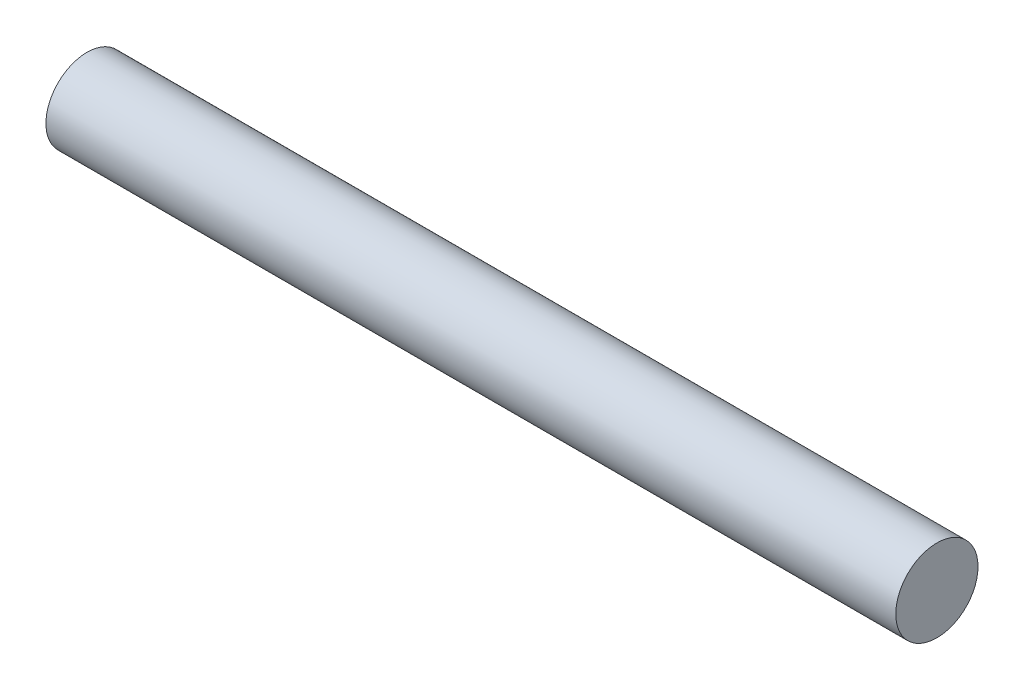
SolidWorks part; units mm, degrees
ref_plane "Front Plane" through (0, 0, 0) normal (0, 0, 1) x (1, 0, 0)
ref_plane "Top Plane" through (0, 0, 0) normal (0, 1, 0) x (1, 0, 0)
ref_plane "Right Plane" through (0, 0, 0) normal (1, 0, 0) x (0, 0, -1)
sketch "Sketch1" plane through (0, 0, 0) normal (1, 0, 0) x (0, 0, -1)
  circle A0 centre (0, 0) radius 4.5
  dimension "D1" = 9
extrude "Boss-Extrude1" add sketch "Sketch1" along normal blind 93
ref_plane "Plane1" through (0, 0, -4.5) normal (0, 0, -1) x (-1, 0, 0)
sketch "Sketch2" plane through (0, 0, -4.5) normal (0, 0, -1) x (-1, 0, 0)
  text T0 "<b>Group 4</b>" font "Century Gothic" height in points 6
extrude "Cut-Extrude1" cut sketch "Sketch2" against normal blind 1
